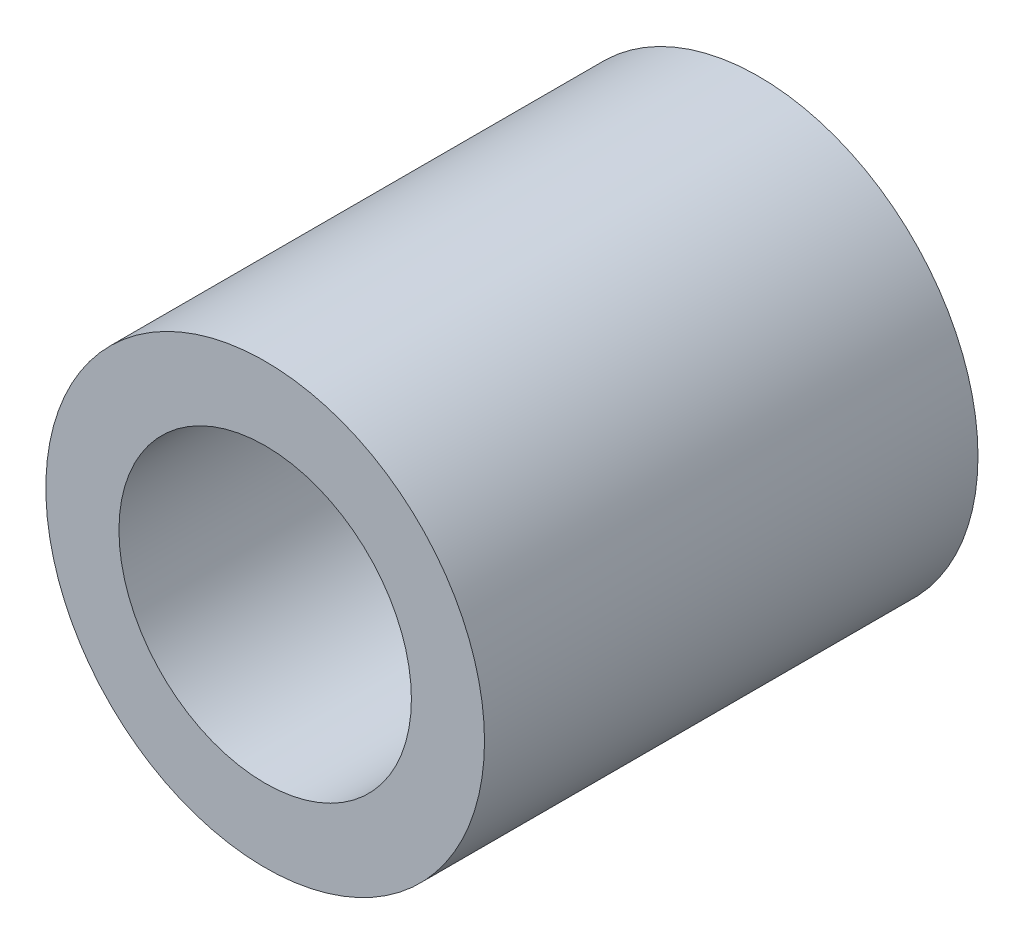
SolidWorks part; units mm, degrees
ref_plane "Front Plane" through (0, 0, 0) normal (0, 0, 1) x (1, 0, 0)
ref_plane "Top Plane" through (0, 0, 0) normal (0, 1, 0) x (1, 0, 0)
ref_plane "Right Plane" through (0, 0, 0) normal (1, 0, 0) x (0, 0, -1)
sketch "Sketch1" plane through (0, 0, 0) normal (0, 0, 1) x (1, 0, 0)
  circle A0 centre (0, 0) radius 2.3813
  circle A1 centre (0, 0) radius 1.5875
  dimension "D1" = 4.7625
  dimension "D2" = 3.175
extrude "Boss-Extrude1" add sketch "Sketch1" along normal blind 5.3578
